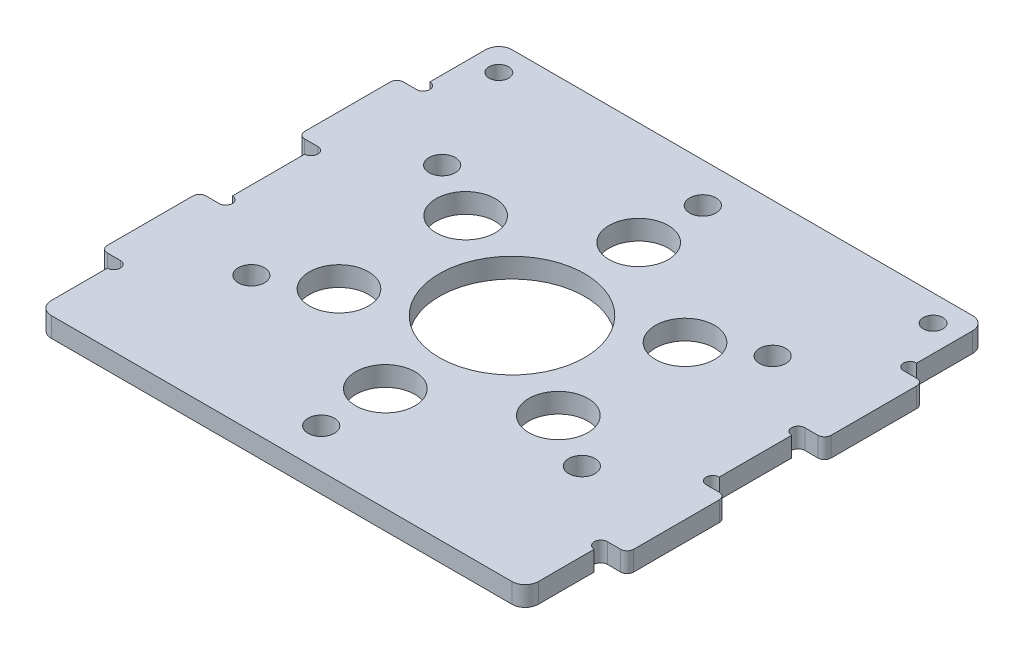
SolidWorks part; units mm, degrees
material "Thornel Mat VMA"
ref_plane "前视基准面" through (0, 0, 0) normal (0, 0, 1) x (1, 0, 0)
ref_plane "上视基准面" through (0, 0, 0) normal (0, 1, 0) x (1, 0, 0)
ref_plane "右视基准面" through (0, 0, 0) normal (1, 0, 0) x (0, 0, -1)
sketch "草图2" plane through (0, 0, 0) normal (0, 1, 0) x (1, 0, 0)
  line L0 (0, 59.627) -> (0, 0) construction
  line L2 (-37, 35) -> (37, 35)
  line L3 (-37, 35) -> (-37, 22.5)
  line L4 (-37, -35) -> (37, -35)
  line L7 (-37, -22.5) -> (-37, -35)
  line L8 (-37, 22.5) -> (-40, 22.5)
  line L10 (-37, 7.5) -> (-40, 7.5)
  line L11 (-40, 22.5) -> (-40, 7.5)
  line L12 (-37, -7.5) -> (-40, -7.5)
  line L14 (-37, -22.5) -> (-40, -22.5)
  line L15 (-40, -7.5) -> (-40, -22.5)
  line L16 (-37, 7.5) -> (-37, -7.5)
  line L17 (-37, 0) -> (0, 0) construction
  line L19 (0, -1.65) -> (0, 1.65) construction
  line L20 (37, 7.5) -> (37, -7.5)
  line L21 (40, -7.5) -> (40, -22.5)
  line L22 (37, -22.5) -> (40, -22.5)
  line L23 (37, -7.5) -> (40, -7.5)
  line L24 (40, 22.5) -> (40, 7.5)
  line L25 (37, 7.5) -> (40, 7.5)
  line L26 (37, 22.5) -> (40, 22.5)
  line L27 (37, -22.5) -> (37, -35)
  line L28 (37, 35) -> (37, 22.5)
  circle A0 centre (0, 0) radius 11.05
  circle A9 centre (0, 29) radius 2
  circle A10 centre (0, 19.25) radius 4.5
  circle A11 centre (0, 0) radius 29 construction
  circle A12 centre (0, 0) radius 19.25 construction
  circle A13 centre (-33, 31) radius 1.5
  circle A14 centre (25.1147, 14.5) radius 2
  circle A15 centre (16.671, 9.625) radius 4.5
  circle A16 centre (25.1147, -14.5) radius 2
  circle A17 centre (16.671, -9.625) radius 4.5
  circle A18 centre (0, -29) radius 2
  circle A19 centre (0, -19.25) radius 4.5
  circle A20 centre (-25.1147, -14.5) radius 2
  circle A21 centre (-16.671, -9.625) radius 4.5
  circle A22 centre (-25.1147, 14.5) radius 2
  circle A23 centre (-16.671, 9.625) radius 4.5
  circle A25 centre (33, 31) radius 1.5
  dimension "D1" = 9
  dimension "D2" = 4
  dimension "D4" = 38.5
  dimension "D5" = 58
  dimension "D6" = 3
  dimension "D8" = 15
  dimension "D10" = 74
  dimension "D11" = 22.1
  dimension "D12" = 4
  dimension "D13" = 4
  dimension "D14" = 3
  dimension "D3" = 6
  dimension "D7" = 15
  dimension "D9" = 70
extrude "凸台-拉伸1" add sketch "草图2" along normal blind 3
sketch "草图3" plane through (0, 3, 0) normal (0, 1, 0) x (1, 0, 0)
  line L0 (-37, 35) -> (-37, 22.5) construction
  line L1 (-37, 7.5) -> (-37, -7.5) construction
  line L2 (-37, -22.5) -> (-37, -35) construction
  line L3 (0, -1.65) -> (0, 1.65) construction
  circle A0 centre (-37, 23.5) radius 1
  circle A1 centre (-37, 6.5) radius 1
  circle A2 centre (-37, -6.5) radius 1
  circle A3 centre (-37, -23.5) radius 1
  circle A4 centre (37, -23.5) radius 1
  circle A5 centre (37, -6.5) radius 1
  circle A6 centre (37, 6.5) radius 1
  circle A7 centre (37, 23.5) radius 1
  dimension "D1" = 2
extrude "切除-拉伸1" cut sketch "草图3" against normal through all
fillet "圆角1" radius 1 8 edges at (40, 1.5, -22.5) (40, 1.5, -7.5) (40, 1.5, 7.5) (40, 1.5, 22.5) (-40, 1.5, 22.5) (-40, 1.5, 7.5) (-40, 1.5, -7.5) (-40, 1.5, -22.5)
fillet "圆角2" radius 2 4 edges at (37, 1.5, -35) (-37, 1.5, -35) (-37, 1.5, 35) (37, 1.5, 35)
